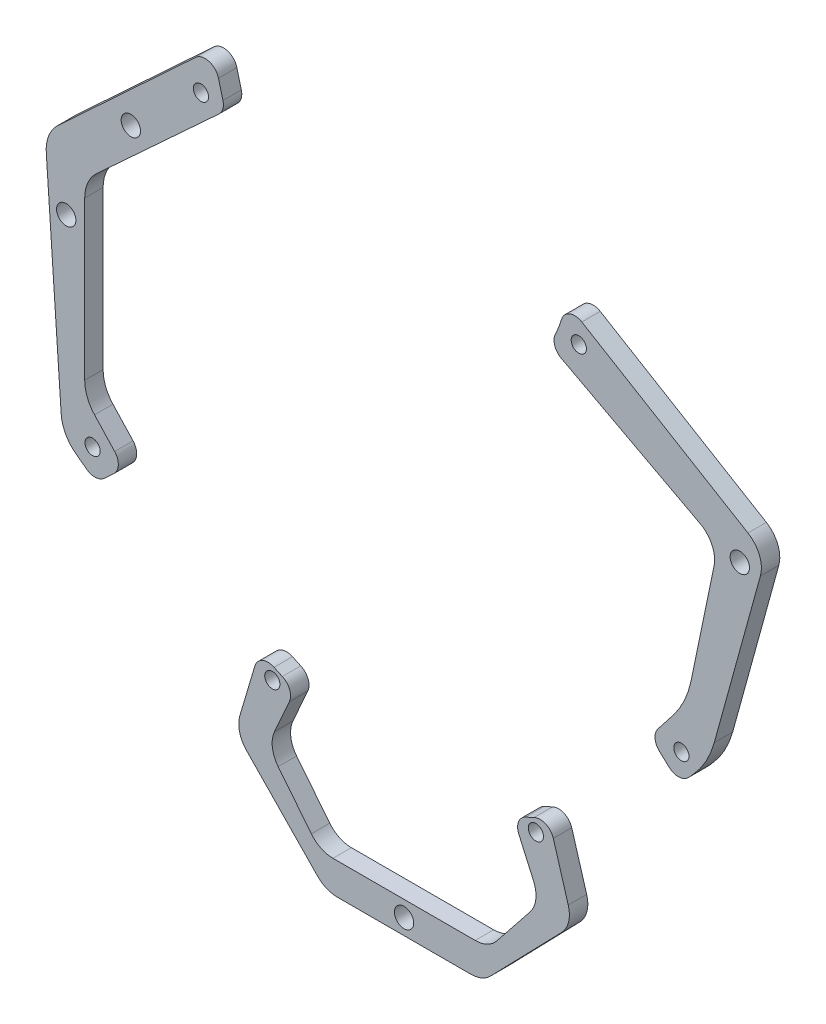
SolidWorks part; units mm, degrees
ref_plane "前视基准面" through (0, 0, 0) normal (0, 0, 1) x (1, 0, 0)
ref_plane "上视基准面" through (0, 0, 0) normal (0, 1, 0) x (1, 0, 0)
ref_plane "右视基准面" through (0, 0, 0) normal (1, 0, 0) x (0, 0, -1)
sketch "草图1" plane through (0, 0, 0) normal (0, 0, 1) x (1, 0, 0)
  line L0 (-38.5525, 24.7998) -> (-44.0596, 45.933) construction
  line L1 (-83.5232, -73.2078) -> (-18.8088, -13.2463) construction
  line L2 (-38.8753, 26.0386) -> (-41.5662, 36.3648)
  line L3 (-66.9096, -57.8144) -> (-60.8015, -52.1549)
  line L4 (-60.8015, -52.1549) -> (-69.3396, -42.94)
  line L5 (-77.024, -57.9032) -> (-42.1229, 10.0563) construction
  line L6 (-69.3396, -42.94) -> (-69.3396, -2.0442)
  line L7 (-69.3396, -2.0442) -> (-38.8753, 26.0386)
  line L8 (-66.9096, -57.8144) -> (-74.1948, -52.3942)
  line L9 (-74.1948, -52.3942) -> (-77.9454, 2.6048)
  line L10 (-77.9454, 2.6048) -> (-41.5662, 36.3648)
  line L11 (0, 0) -> (0, 80.5084) construction
  line L20 (83.5232, -73.2078) -> (18.8088, -13.2463) construction
  line L21 (59.7157, -51.1488) -> (53.4161, -45.3119)
  line L22 (34.3146, 23.8869) -> (40.1937, 46.4474) construction
  line L23 (34.3146, 23.8869) -> (35.1669, 27.1576)
  line L24 (53.4161, -45.3119) -> (61.3412, -35.1543)
  line L25 (39.5494, 7.2787) -> (69.3928, -50.8324) construction
  line L26 (61.3412, -35.1543) -> (68.2102, -2.0442)
  line L27 (68.2102, -2.0442) -> (31.3768, 17.5057)
  line L28 (59.7157, -51.1488) -> (66.0464, -44.3163)
  line L29 (66.0464, -44.3163) -> (78.5691, 1.1241)
  line L30 (78.5691, 1.1241) -> (35.1669, 27.1576)
  line L31 (31.3768, -71.6277) -> (36.6419, -89.357)
  line L32 (36.6419, -89.357) -> (17.0283, -109.5812)
  line L33 (17.0283, -109.5812) -> (-17.0283, -109.5812)
  line L34 (23.652, -75.2126) -> (29.6121, -88.5989)
  line L35 (29.6121, -88.5989) -> (18.3332, -102.7477)
  line L36 (18.3332, -102.7477) -> (-18.3332, -102.7477)
  line L37 (-29.6121, -88.5989) -> (-18.3332, -102.7477)
  line L38 (-23.652, -75.2126) -> (-29.6121, -88.5989)
  line L39 (-36.6419, -89.357) -> (-17.0283, -109.5812)
  line L40 (-31.3768, -71.6277) -> (-36.6419, -89.357)
  line L41 (0, -109.5812) -> (0, -102.7477) construction
  arc A0 (14.9609, 8.9302) -> (34.3146, 23.8869) centre (14.9609, 28.9302) ccw construction
  arc A1 (31.3768, 17.5057) -> (34.3146, 23.8869) centre (14.9609, 28.9302) ccw
  circle A2 centre (0, -106.1644) radius 7
  arc A3 (-32.6432, -70.9182) -> (32.6432, -70.9182) centre (0, -14.1321) ccw construction
  arc A4 (23.652, -75.2126) -> (31.3768, -71.6277) centre (0, -14.1321) ccw
  arc A5 (-31.3768, -71.6277) -> (-23.652, -75.2126) centre (0, -14.1321) ccw
  circle A6 centre (-73.356, -10.6943) radius 7 construction
  circle A7 centre (-59.3267, 13.1036) radius 7 construction
  circle A8 centre (72.8924, -2.9246) radius 7 construction
  circle A9 centre (0, -106.1644) radius 2.1
  circle A10 centre (-73.356, -10.6943) radius 2.1
  circle A11 centre (-59.3267, 13.1036) radius 2.1
  circle A12 centre (72.8924, -2.9246) radius 2.1
  circle A13 centre (60.2014, -44.9335) radius 1.65 construction
  circle A14 centre (60.2014, -44.9335) radius 1.65
  circle A15 centre (-28.6101, -75.8204) radius 1.65 construction
  circle A16 centre (28.6101, -75.8204) radius 1.65 construction
  circle A17 centre (-28.6101, -75.8204) radius 1.65
  circle A18 centre (28.6101, -75.8204) radius 1.65
  circle A19 centre (-67.6329, -51.4873) radius 1.65 construction
  circle A20 centre (-67.6329, -51.4873) radius 1.65
  circle A21 centre (-44.1, 26.89) radius 1.65 construction
  circle A22 centre (37.9298, 20.5529) radius 1.65 construction
  circle A23 centre (-44.1, 26.89) radius 1.65
  circle A24 centre (37.9298, 20.5529) radius 1.65
  point P45 (0, -102.7477)
  point P48 (0, -109.5812)
  dimension "D1" = 14
  dimension "D2" = 14
  dimension "D3" = 14
  dimension "D4" = 14
  dimension "D5" = 4.2
  dimension "D6" = 4.2
  dimension "D7" = 4.2
  dimension "D8" = 4.2
extrude "凸台-拉伸1" add sketch "草图1" along normal blind 4 contours L10 L9 L8 L3 L4 L6 L7 L2 A23 A20 A11 A10 | A1 L27 L26 L24 L21 L28 L29 L30 L23 A24 A14 A12 | A4 L34 L35 L36 A2 L33 L32 L31 A18 | A5 L40 L39 L33 A2 L36 L37 L38 A17 | L36 A2 L33 A9
fillet "圆角1" radius 20 2 edges at (66.0464, -44.3163, 2) (61.3412, -35.1543, 2)
fillet "圆角2" radius 3 2 edges at (53.4161, -45.3119, 2) (59.7157, -51.1488, 2)
fillet "圆角3" radius 6 2 edges at (78.5691, 1.1241, 2) (68.2102, -2.0442, 2)
fillet "圆角4" radius 3 2 edges at (35.1669, 27.1576, 2) (31.3768, 17.5057, 2)
fillet "圆角5" radius 3 4 edges at (-31.3768, -71.6277, 2) (-23.652, -75.2126, 2) (31.3768, -71.6277, 2) (23.652, -75.2126, 2)
fillet "圆角6" radius 6 4 edges at (-36.6419, -89.357, 2) (-29.6121, -88.5989, 2) (36.6419, -89.357, 2) (29.6121, -88.5989, 2)
fillet "圆角7" radius 6 4 edges at (-17.0283, -109.5812, 2) (17.0283, -109.5812, 2) (-18.3332, -102.7477, 2) (18.3332, -102.7477, 2)
fillet "圆角8" radius 3 4 edges at (-41.5662, 36.3648, 2) (-38.8753, 26.0386, 2) (-66.9096, -57.8144, 2) (-60.8015, -52.1549, 2)
fillet "圆角9" radius 8 4 edges at (-74.1948, -52.3942, 2) (-77.9454, 2.6048, 2) (-69.3396, -2.0442, 2) (-69.3396, -42.94, 2)
